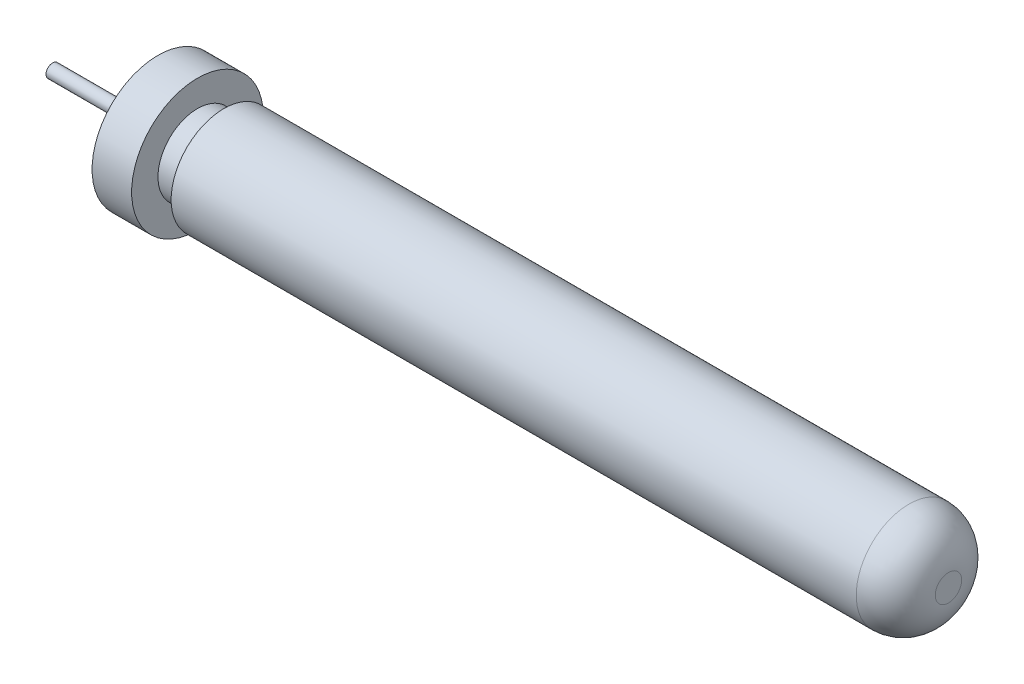
SolidWorks part; units mm, degrees
ref_plane "Спереди" through (0, 0, 0) normal (0, 0, 1) x (1, 0, 0)
ref_plane "Сверху" through (0, 0, 0) normal (0, 1, 0) x (1, 0, 0)
ref_plane "Справа" through (0, 0, 0) normal (1, 0, 0) x (0, 0, -1)
sketch "Эскиз1" plane through (0, 0, 0) normal (0, 0, 1) x (1, 0, 0)
  line L0 (0, 0) -> (0, 0.5)
  line L1 (0, 0.5) -> (6, 0.5)
  line L2 (6, 2) -> (8, 2)
  line L3 (8, 2) -> (8, 5)
  line L4 (8, 5) -> (11, 5)
  line L5 (11, 5) -> (11, 3)
  line L6 (11, 3) -> (13, 3)
  line L7 (13, 3) -> (13, 4)
  line L8 (13, 4) -> (68, 4)
  line L9 (68, 4) -> (68, 0)
  line L10 (68, 0) -> (0, 0)
  line L11 (6, 2) -> (6, 0.5)
  dimension "D1" = 0.5
  dimension "D2" = 6
  dimension "D3" = 55
  dimension "D4" = 4
  dimension "D5" = 3
  dimension "D6" = 5
  dimension "D7" = 2
  dimension "D8" = 2
  dimension "D9" = 3
  dimension "D10" = 2
revolve "Повернуть1" add sketch "Эскиз1" angle 360 about L10
fillet "Скругление1" radius 3 1 edges at (68, 0, -4)
